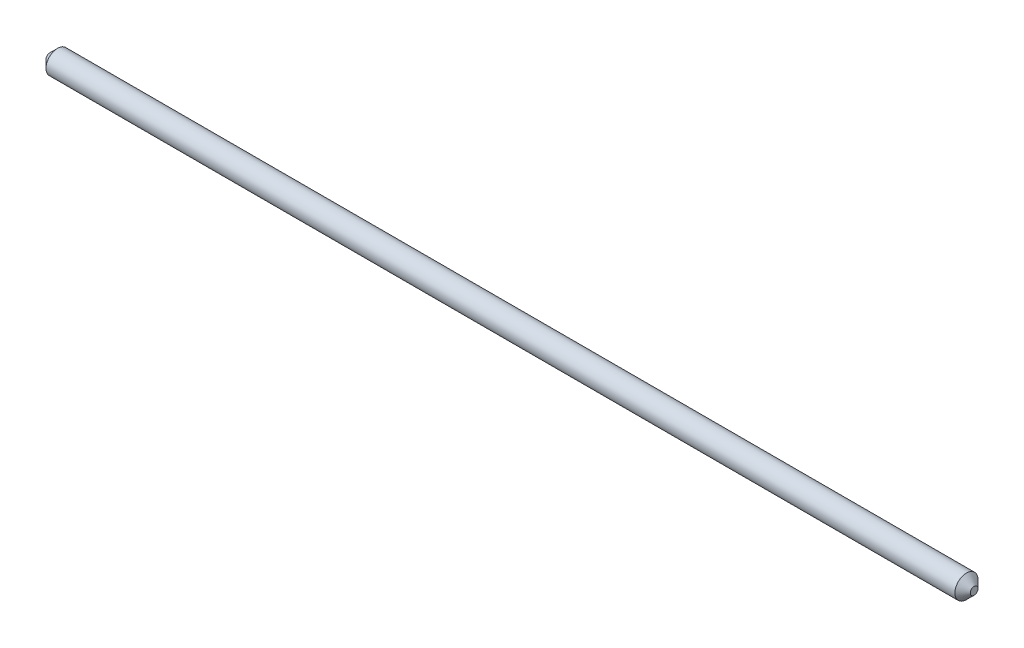
SolidWorks part; units mm, degrees
ref_plane "Front Plane" through (0, 0, 0) normal (0, 0, 1) x (1, 0, 0)
ref_plane "Top Plane" through (0, 0, 0) normal (0, 1, 0) x (1, 0, 0)
ref_plane "Right Plane" through (0, 0, 0) normal (1, 0, 0) x (0, 0, -1)
sketch "Sketch1" plane through (0, 0, 0) normal (1, 0, 0) x (0, 0, -1)
  circle A0 centre (0, 0) radius 1.5
  dimension "D1" = 3
extrude "Boss-Extrude1" add sketch "Sketch1" along normal mid plane 120
chamfer "Chamfer1" distance 1 angle 45 2 edges at (-60, 0, -1.5) (60, 0, -1.5)
